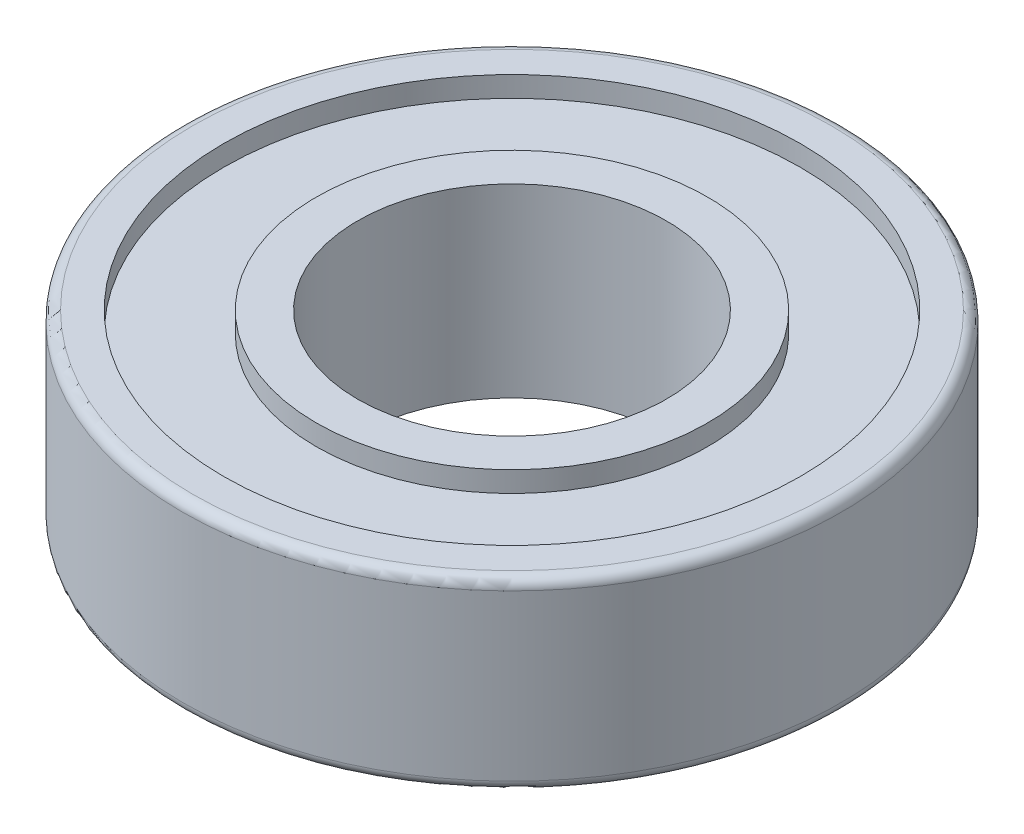
SolidWorks part; units mm, degrees
ref_plane "Plan de face" through (0, 0, 0) normal (0, 0, 1) x (1, 0, 0)
ref_plane "Plan de dessus" through (0, 0, 0) normal (0, 1, 0) x (1, 0, 0)
ref_plane "Plan de droite" through (0, 0, 0) normal (1, 0, 0) x (0, 0, -1)
ref_axis "Axe1" through (0, 4.95, 0) along (0, -1, 0)
sketch "Disque_Intérieur" plane through (0, 0, 0) normal (0, 0, 1) x (1, 0, 0)
  line L1 (7.5, -4.5) -> (9.5, -4.5)
  line L2 (7.5, -4.5) -> (7.5, 4.5)
  line L3 (7.5, 4.5) -> (9.5, 4.5)
  line L4 (9.5, -4.5) -> (9.5, 4.5)
  line L5 (7.5, -4.5) -> (9.5, 4.5) construction
  line L6 (7.5, 4.5) -> (9.5, -4.5) construction
  point P0 (8.5, 0)
  dimension "D1" = 2
  dimension "D2" = 9
  dimension "D3" = 7.5
revolve "Révolution1_Disque_Intérieur" add sketch "Disque_Intérieur" angle 360 about axis through (0, 4.95, 0) along (0, -1, 0)
sketch "Disque_extérieur" plane through (0, 0, 0) normal (0, 0, 1) x (1, 0, 0)
  line L1 (14, -4.5) -> (16, -4.5)
  line L2 (14, -4.5) -> (14, 4.5)
  line L3 (14, 4.5) -> (16, 4.5)
  line L4 (16, -4.5) -> (16, 4.5)
  line L5 (14, -4.5) -> (16, 4.5) construction
  line L6 (14, 4.5) -> (16, -4.5) construction
  line L7 (10.45, 0) -> (-10.45, 0) construction
  line L8 (0, -4.95) -> (0, 4.95) construction
  point P0 (15, 0)
  dimension "D1" = 2
  dimension "D2" = 9
  dimension "D3" = 14
revolve "Révolution2_Disque_extérieur" add sketch "Disque_extérieur" angle 360 about axis through (0, 4.95, 0) along (0, -1, 0)
sketch "Disque_Intermédiaire" plane through (0, 0, 0) normal (0, 0, 1) x (1, 0, 0)
  line L0 (55, 0) -> (-55, 0) construction
  line L1 (9.5, -3.5) -> (14, -3.5)
  line L2 (9.5, -3.5) -> (9.5, 3.5)
  line L3 (9.5, 3.5) -> (14, 3.5)
  line L4 (14, -3.5) -> (14, 3.5)
  line L5 (9.5, -3.5) -> (14, 3.5) construction
  line L6 (9.5, 3.5) -> (14, -3.5) construction
  line L7 (14, -4.5) -> (14, 4.5) construction
  line L8 (9.5, -4.5) -> (9.5, 4.5) construction
  line L10 (16, 4.5) -> (-16, 4.5) construction
  point P0 (11.75, 0)
  dimension "D1" = 1
revolve "Révolution3_Disque_Intermédiaire" add sketch "Disque_Intermédiaire" angle 360 about axis through (0, 4.95, 0) along (0, -1, 0)
fillet "Congé1_Disque_extérieur_0.5mm" radius 0.5 2 edges at (0, -4.5, 16) (0, 4.5, 16)
